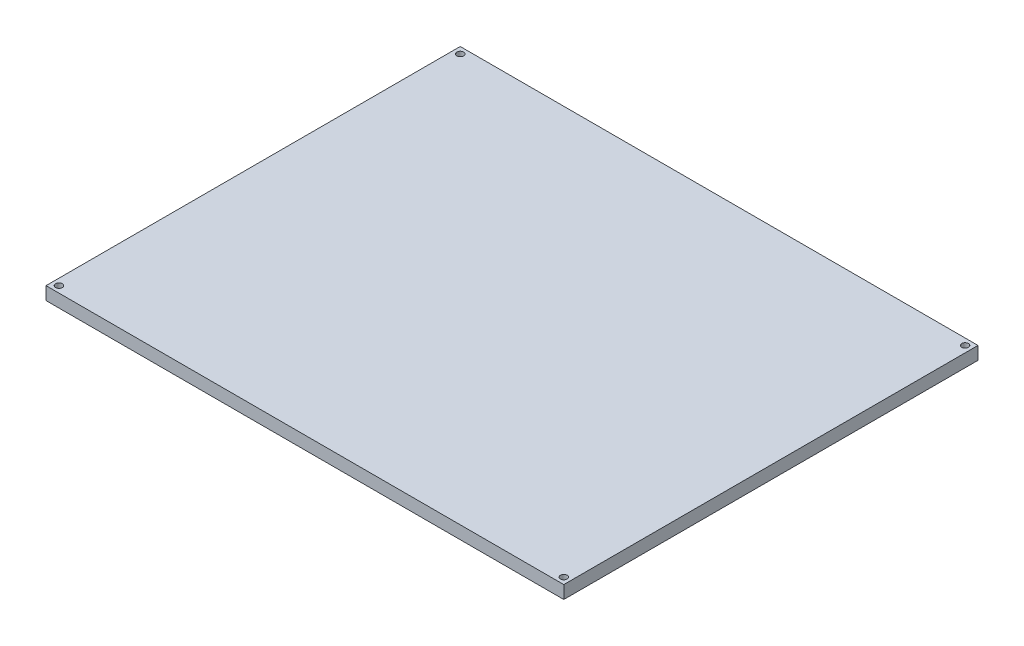
SolidWorks part; units mm, degrees
ref_plane "Front Plane" through (0, 0, 0) normal (0, 0, 1) x (1, 0, 0)
ref_plane "Top Plane" through (0, 0, 0) normal (0, 1, 0) x (1, 0, 0)
ref_plane "Right Plane" through (0, 0, 0) normal (1, 0, 0) x (0, 0, -1)
sketch "Sketch1" plane through (0, 0, 0) normal (0, 1, 0) x (1, 0, 0)
  line L1 (-127, -101.6) -> (127, -101.6)
  line L2 (-127, -101.6) -> (-127, 101.6)
  line L3 (-127, 101.6) -> (127, 101.6)
  line L4 (127, -101.6) -> (127, 101.6)
  line L5 (-127, -101.6) -> (127, 101.6) construction
  line L6 (-127, 101.6) -> (127, -101.6) construction
  point P0 (0, 0)
  dimension "D1" = 254
  dimension "D2" = 203.2
extrude "Boss-Extrude1" add sketch "Sketch1" along normal blind 6.35
sketch "Sketch3" plane through (0, 6.35, 0) normal (0, 1, 0) x (1, 0, 0)
  circle A8 centre (123.825, 98.425) radius 1.65 construction
  circle A9 centre (123.825, -98.425) radius 1.65 construction
  circle A10 centre (-123.825, -98.425) radius 1.65 construction
  circle A11 centre (-123.825, 98.425) radius 1.65 construction
  circle A12 centre (123.825, 98.425) radius 1.65
  circle A13 centre (123.825, -98.425) radius 1.65
  circle A14 centre (-123.825, -98.425) radius 1.65
  circle A15 centre (-123.825, 98.425) radius 1.65
extrude "Cut-Extrude1" cut sketch "Sketch3" against normal through all
